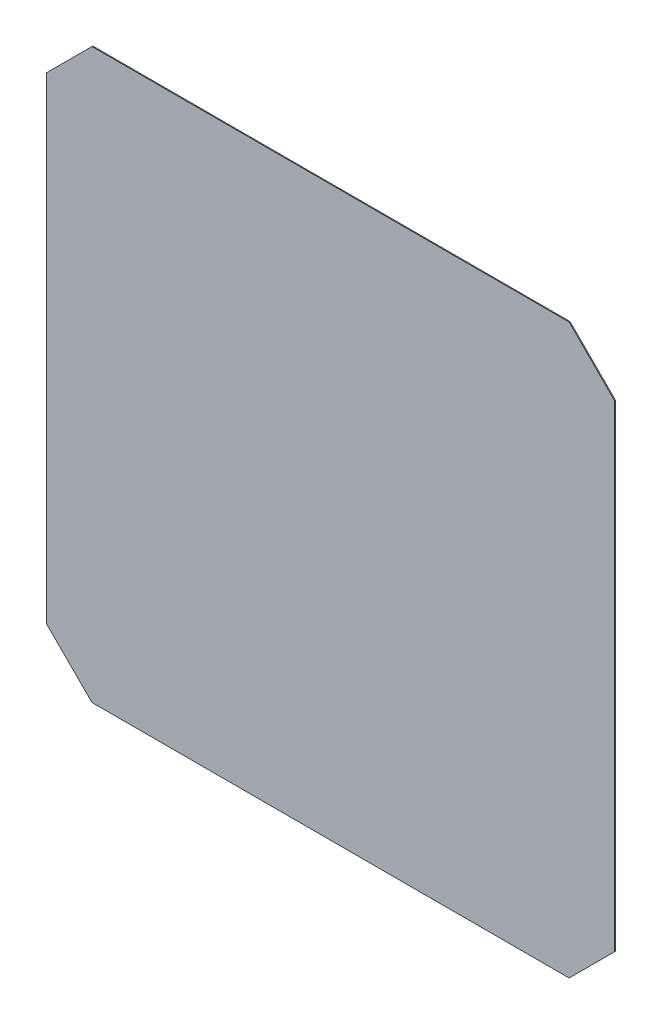
SolidWorks part; units mm, degrees
material "硅"
ref_plane "前视基准面" through (0, 0, 0) normal (0, 0, 1) x (1, 0, 0)
ref_plane "上视基准面" through (0, 0, 0) normal (0, 1, 0) x (1, 0, 0)
ref_plane "右视基准面" through (0, 0, 0) normal (1, 0, 0) x (0, 0, -1)
other "Configuration Table"
sketch "草图1" plane through (0, 0, 0) normal (0, 0, 1) x (1, 0, 0)
  line L0 (52.5, 62.5) -> (62.5, 52.5)
  line L1 (-52.5, 62.5) -> (52.5, 62.5)
  line L2 (-62.5, 52.5) -> (-62.5, -52.5)
  line L3 (-52.5, -62.5) -> (52.5, -62.5)
  line L4 (62.5, 52.5) -> (62.5, -52.5)
  line L5 (-62.5, 62.5) -> (62.5, -62.5) construction
  line L6 (-62.5, -62.5) -> (62.5, 62.5) construction
  line L7 (-62.5, -52.5) -> (-52.5, -62.5)
  line L8 (52.5, -62.5) -> (62.5, -52.5)
  line L9 (-62.5, 52.5) -> (-52.5, 62.5)
  point P0 (0, 0)
  dimension "D1" = 125
  dimension "D2" = 125
extrude "凸台-拉伸1" add sketch "草图1" along normal blind 0.2
